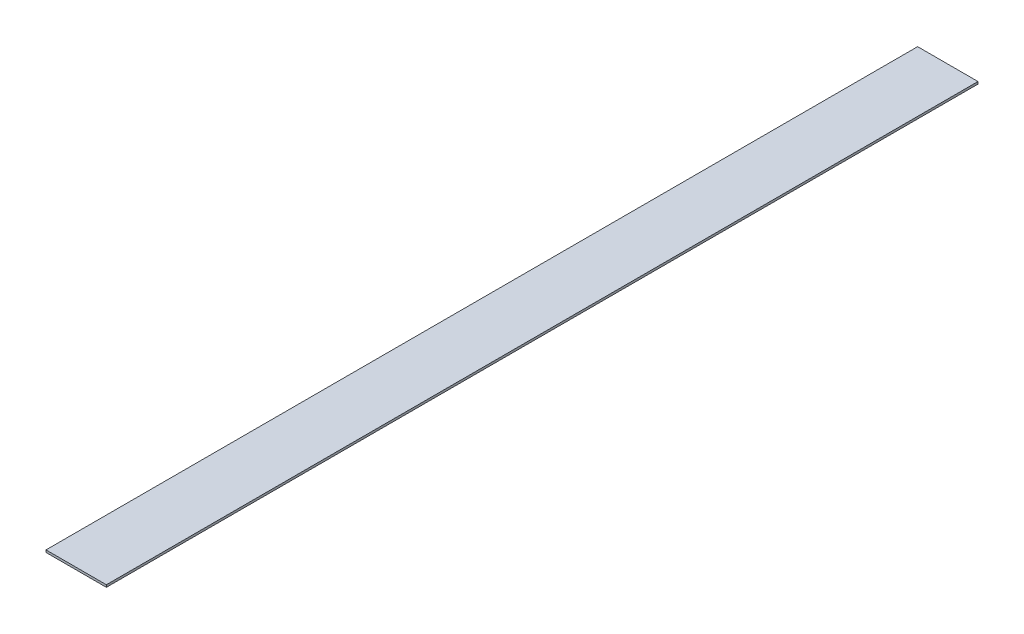
SolidWorks part; units mm, degrees
material "AISI 1020 Acier laminé à froid"
ref_plane "Plan de face" through (0, 0, 0) normal (0, 0, 1) x (1, 0, 0)
ref_plane "Plan de dessus" through (0, 0, 0) normal (0, 1, 0) x (1, 0, 0)
ref_plane "Plan de droite" through (0, 0, 0) normal (1, 0, 0) x (0, 0, -1)
sketch "Esquisse1" plane through (0, 0, 0) normal (0, 0, 1) x (1, 0, 0)
  line L1 (0, 0) -> (40, 0)
  line L2 (0, 0) -> (0, 1.5)
  line L3 (0, 1.5) -> (40, 1.5)
  line L4 (40, 0) -> (40, 1.5)
  dimension "D1" = 40
  dimension "D2" = 1.5
extrude "Boss.-Extru.1" add sketch "Esquisse1" along normal blind 577.5
